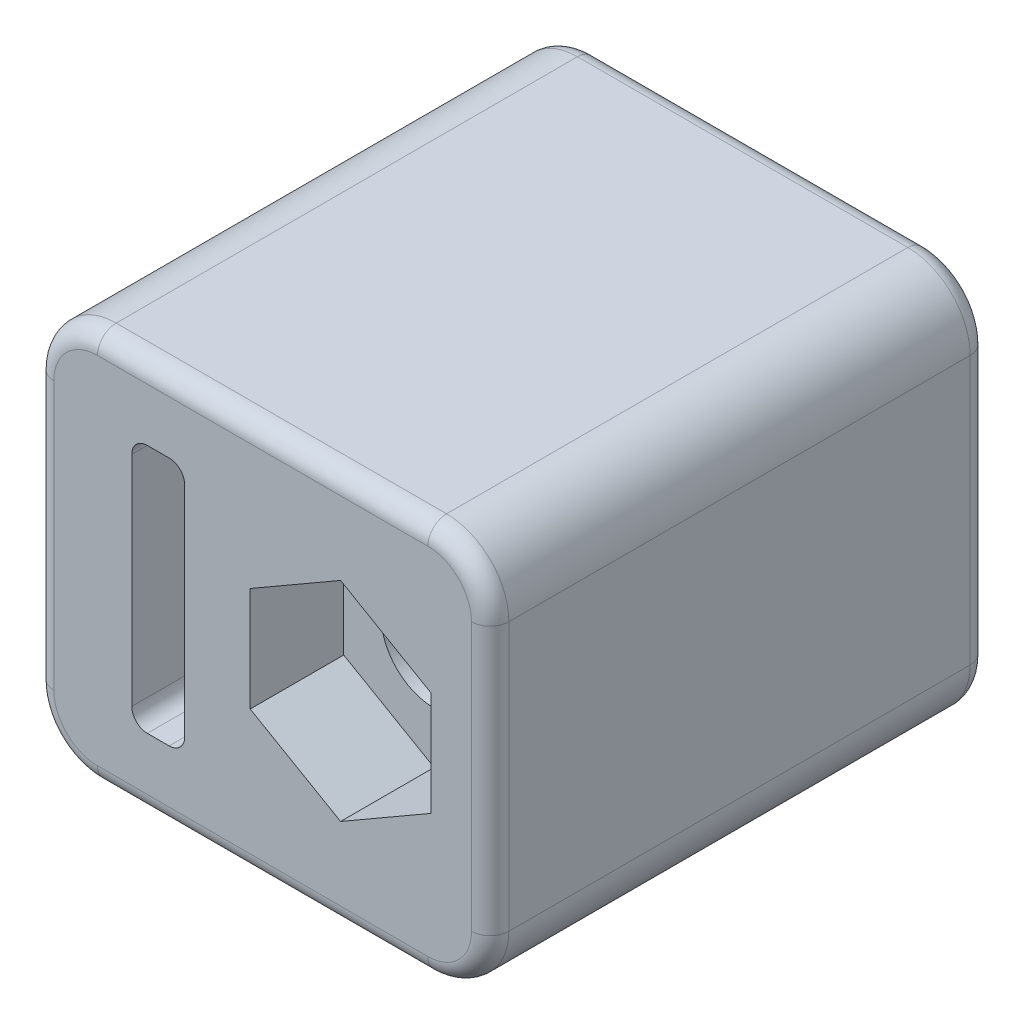
SolidWorks part; units mm, degrees
ref_plane "Front Plane" through (0, 0, 0) normal (0, 0, 1) x (1, 0, 0)
ref_plane "Top Plane" through (0, 0, 0) normal (0, 1, 0) x (1, 0, 0)
ref_plane "Right Plane" through (0, 0, 0) normal (1, 0, 0) x (0, 0, -1)
sketch "Sketch1" plane through (0, 0, 0) normal (0, 0, 1) x (1, 0, 0)
  line L8 (3.1, 9.8) -> (3.1, 2.8)
  line L9 (3.6, 2.3) -> (4.3, 2.3)
  line L10 (4.8, 2.8) -> (4.8, 9.8)
  line L15 (3.6, 10.3) -> (4.3, 10.3)
  line L18 (2, 0) -> (12.6, 0)
  line L19 (0, 2) -> (0, 10.6)
  line L20 (2, 12.6) -> (12.6, 12.6)
  line L21 (14.6, 2) -> (14.6, 10.6)
  arc A13 (3.6, 10.3) -> (3.1, 9.8) centre (3.6, 9.8) ccw
  arc A14 (4.3, 10.3) -> (4.8, 9.8) centre (4.3, 9.8) cw
  arc A15 (3.1, 2.8) -> (3.6, 2.3) centre (3.6, 2.8) ccw
  arc A16 (4.8, 2.8) -> (4.3, 2.3) centre (4.3, 2.8) cw
  circle A17 centre (9.8, 6.3) radius 1.7
  arc A18 (12.6, 12.6) -> (14.6, 10.6) centre (12.6, 10.6) cw
  arc A19 (12.6, 0) -> (14.6, 2) centre (12.6, 2) ccw
  arc A20 (2, 0) -> (0, 2) centre (2, 2) cw
  arc A21 (0, 10.6) -> (2, 12.6) centre (2, 10.6) cw
  point P26 (0, 0)
extrude "Boss-Extrude1" add sketch "Sketch1" along normal blind 16
sketch "Sketch2" plane through (0, 0, 16) normal (0, 0, 1) x (1, 0, 0)
  line L1 (9.8, 9.6486) -> (6.9, 7.9743)
  line L2 (6.9, 7.9743) -> (6.9, 4.6257)
  line L3 (6.9, 4.6257) -> (9.8, 2.9514)
  line L4 (9.8, 2.9514) -> (12.7, 4.6257)
  line L5 (12.7, 4.6257) -> (12.7, 7.9743)
  line L6 (12.7, 7.9743) -> (9.8, 9.6486)
  circle A0 centre (9.8, 6.3) radius 2.9 construction
extrude "Cut-Extrude1" cut sketch "Sketch2" against normal blind 3
sketch "Sketch3" plane through (0, 0, 0) normal (0, 0, -1) x (-1, 0, 0)
  line L0 (-4.8, 9.8) -> (-4.8, 2.8)
  line L1 (-4.3, 2.3) -> (-2.8, 2.3)
  line L2 (-2.3, 2.8) -> (-2.3, 9.8)
  line L3 (-2.8, 10.3) -> (-4.3, 10.3)
  arc A0 (-4.8, 9.8) -> (-4.3, 10.3) centre (-4.3, 9.8) cw
  arc A1 (-2.8, 10.3) -> (-2.3, 9.8) centre (-2.8, 9.8) cw
  arc A2 (-4.8, 2.8) -> (-4.3, 2.3) centre (-4.3, 2.8) ccw
  arc A3 (-2.3, 2.8) -> (-2.8, 2.3) centre (-2.8, 2.8) cw
extrude "Cut-Extrude2" cut sketch "Sketch3" against normal blind 8
fillet "Fillet1" radius 0.6 16 edges at (14.0142, 12.0142, 0) (14.6, 6.3, 0) (14.0142, 0.5858, 0) (7.3, 0, 0) (0.5858, 0.5858, 0) (0, 6.3, 0) (0.5858, 12.0142, 0) (14.0142, 12.0142, 16) (14.6, 6.3, 16) (14.0142, 0.5858, 16) (7.3, 0, 16) (0.5858, 0.5858, 16) (0, 6.3, 16) (0.5858, 12.0142, 16) (7.3, 12.6, 0) (7.3, 12.6, 16)
